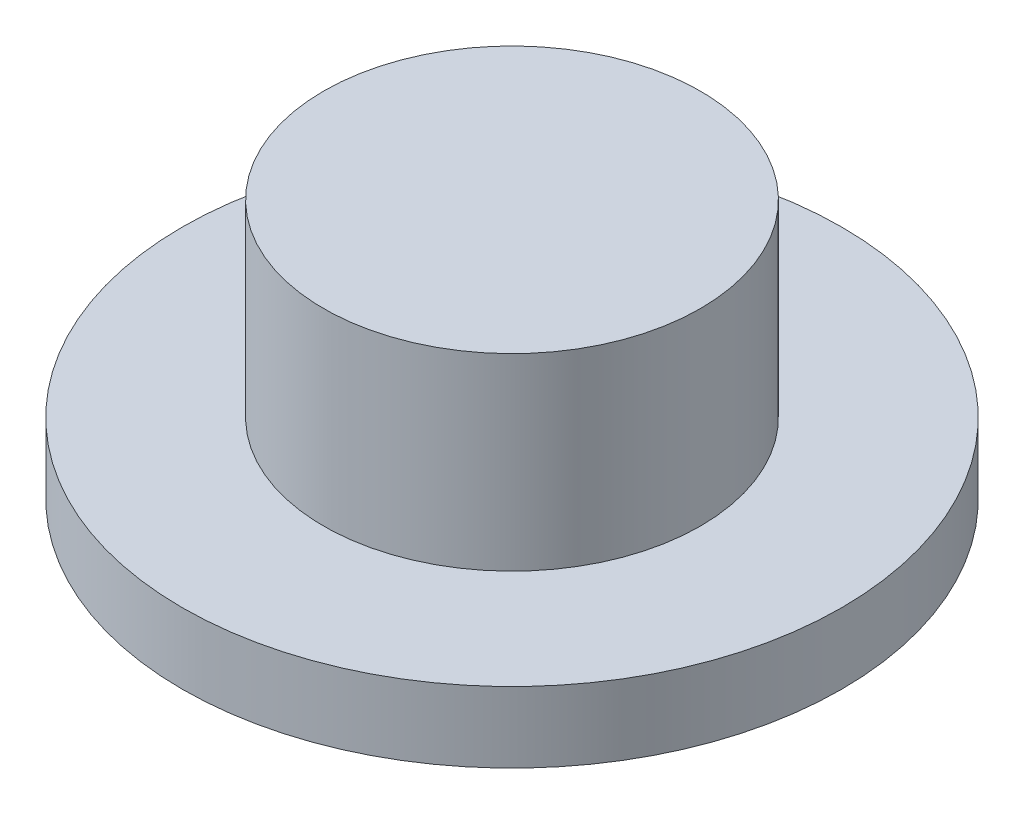
SolidWorks part; units mm, degrees
ref_plane "Front Plane" through (0, 0, 0) normal (0, 0, 1) x (1, 0, 0)
ref_plane "Top Plane" through (0, 0, 0) normal (0, 1, 0) x (1, 0, 0)
ref_plane "Right Plane" through (0, 0, 0) normal (1, 0, 0) x (0, 0, -1)
sketch "Sketch1" plane through (0, 0, 0) normal (0, 0, 1) x (1, 0, 0)
  line L1 (0, 5.5) -> (4, 5.5)
  line L2 (4, 5.5) -> (4, 1.5)
  line L3 (4, 1.5) -> (7, 1.5)
  line L4 (7, 1.5) -> (7, 0)
  line L6 (0, 5.5) -> (0, 6.9292) construction
  line L7 (0, 5.5) -> (0, 1)
  line L8 (0, 1) -> (1.75, 1)
  line L9 (1.75, 1) -> (2, 0)
  line L10 (2, 0) -> (7, 0)
  line L11 (0, 1) -> (0, 0) construction
  line L12 (0, 0) -> (2, 0) construction
  point P10 (1.8117, 1)
  dimension "D1" = 4
  dimension "D2" = 3
  dimension "D3" = 4
  dimension "D4" = 1.5
  dimension "D5" = 2
  dimension "D6" = 1
  dimension "D7" = 1.75
revolve "Revolve1" add sketch "Sketch1" angle 360 about L6
